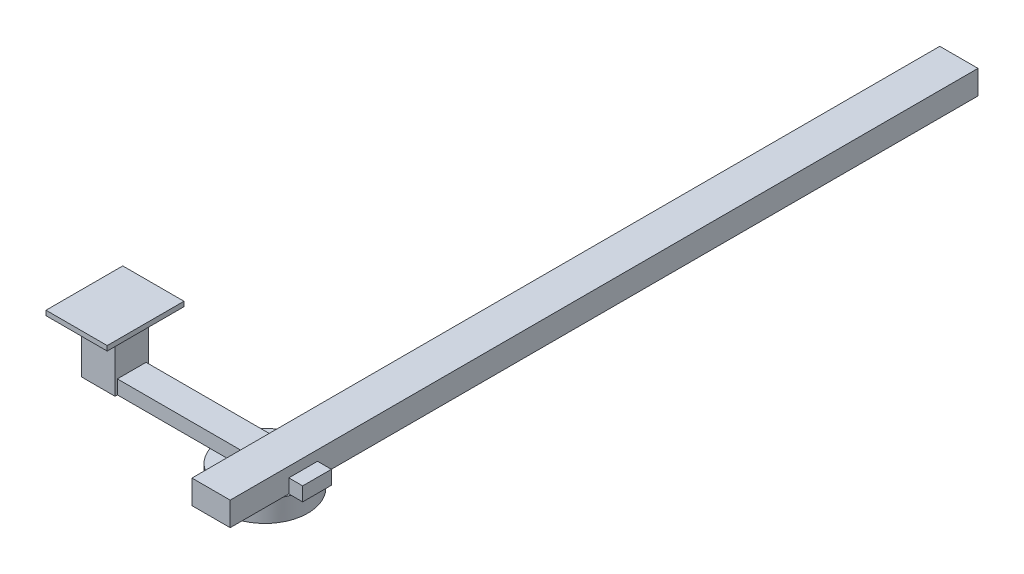
SolidWorks part; units mm, degrees
ref_plane "Plan de face" through (0, 0, 0) normal (0, 0, 1) x (1, 0, 0)
ref_plane "Plan de dessus" through (0, 0, 0) normal (0, 1, 0) x (1, 0, 0)
ref_plane "Plan de droite" through (0, 0, 0) normal (1, 0, 0) x (0, 0, -1)
sketch "Esquisse1" plane through (0, 0, 0) normal (0, 0, 1) x (1, 0, 0)
  line L0 (0, 0) -> (90, 0)
  line L1 (90, 0) -> (90, 45)
  line L2 (90, 45) -> (0, 45)
  line L3 (0, 45) -> (0, 0)
  dimension "D1" = 90
  dimension "D2" = 45
revolve "Révolution1" add sketch "Esquisse1" angle 360 about L3
sketch "Esquisse2" plane through (0, 45, 0) normal (0, 1, 0) x (1, 0, 0)
  line L1 (0, 1411.1242) -> (79.9507, 1411.1242)
  line L2 (0, 1411.1242) -> (0, -152.582)
  line L3 (0, -152.582) -> (79.9507, -152.582)
  line L4 (79.9507, 1411.1242) -> (79.9507, -152.582)
  point P4 (64.1623, -105.9552)
  point P5 (65.6813, -131.2055)
extrude "Boss.-Extru.1" add sketch "Esquisse2" along normal blind 50
sketch "Esquisse3" plane through (0, 45, 0) normal (0, 1, 0) x (1, 0, 0)
  line L0 (0, 1411.1242) -> (0, -152.582) construction
  line L1 (-278.5, 30) -> (0, 30)
  line L2 (-348.5, 30) -> (-348.5, -30)
  line L3 (-278.5, -30) -> (0, -30)
  line L4 (0, 30) -> (0, -30)
  line L5 (-348.5, -30) -> (-348.5, -35)
  line L6 (-348.5, 35) -> (-278.5, 35)
  line L7 (-348.5, 35) -> (-348.5, 30)
  line L9 (-278.5, 35) -> (-278.5, 30)
  line L10 (-348.5, -35) -> (-278.5, -35)
  line L11 (-278.5, -35) -> (-278.5, -30)
  dimension "D1" = 70
  dimension "D2" = 60
  dimension "D3" = 30
  dimension "D4" = 60
  dimension "D5" = 5
  dimension "D6" = 348.5
  dimension "D7" = 5
extrude "Boss.-Extru.2" add sketch "Esquisse3" along normal blind 29
sketch "Esquisse5" plane through (79.9507, 0, 0) normal (1, 0, 0) x (0, 0, -1)
  line L0 (41.3265, 45) -> (-41.3265, 45) construction
  line L1 (-30, 74) -> (30, 74)
  line L2 (-30, 74) -> (-30, 45)
  line L3 (-30, 45) -> (30, 45)
  line L4 (30, 74) -> (30, 45)
  line L5 (30, 74) -> (30, 45) construction
extrude "Boss.-Extru.3" add sketch "Esquisse5" along normal blind 29
sketch "Esquisse6" plane through (0, 74, 0) normal (0, 1, 0) x (1, 0, 0)
  line L0 (-278.5, -30) -> (0, -30) construction
  line L1 (-348.5, 35) -> (-278.5, 35)
  line L2 (-348.5, 35) -> (-348.5, -30)
  line L4 (-278.5, 35) -> (-278.5, -30)
  line L5 (-278.5, 30) -> (-278.5, 35) construction
  line L6 (-348.5, -30) -> (-348.5, -35)
  line L7 (-348.5, -35) -> (-278.5, -35)
  line L8 (-278.5, -35) -> (-278.5, -30)
extrude "Boss.-Extru.4" add sketch "Esquisse6" along normal blind 90
sketch "Esquisse9" plane through (0, 164, 0) normal (0, 1, 0) x (1, 0, 0)
  line L0 (-278.5, 30) -> (-278.5, -30) construction
  line L8 (-278.5, 35) -> (-348.5, 35) construction
  line L10 (-377.5, 80.25) -> (-249.5, 80.25)
  line L11 (-377.5, 80.25) -> (-377.5, -80.25)
  line L12 (-377.5, -80.25) -> (-249.5, -80.25)
  line L13 (-249.5, 80.25) -> (-249.5, -80.25)
  dimension "D1" = 128
  dimension "D2" = 29
  dimension "D3" = 160.5
  dimension "D4" = 45.25
extrude "Boss.-Extru.5" add sketch "Esquisse9" along normal blind 10
